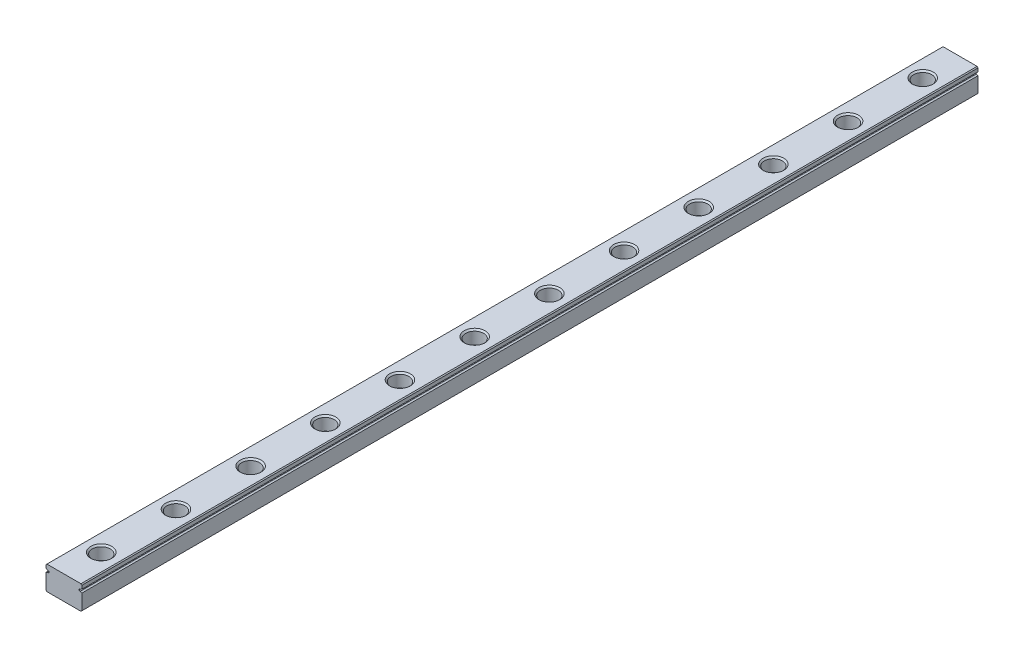
SolidWorks part; units mm, degrees
material "AISI 1045 鋼，冷拉"
ref_plane "Front Plane" through (0, 0, 0) normal (0, 0, 1) x (1, 0, 0)
ref_plane "Top Plane" through (0, 0, 0) normal (0, 1, 0) x (1, 0, 0)
ref_plane "Right Plane" through (0, 0, 0) normal (1, 0, 0) x (0, 0, -1)
sketch "Sketch1" plane through (0, 0, 0) normal (0, 0, 1) x (1, 0, 0)
  line L0 (-6, -4) -> (-6, 4) construction
  line L1 (-6, 4) -> (6, 4)
  line L2 (-6, -4) -> (6, -4)
  line L3 (-6, 4) -> (-6, 2.75)
  line L4 (-6, 2.75) -> (-5.5, 2.25) construction
  line L5 (-5.5, 2.25) -> (-5, 2.25)
  line L6 (-5.5, 1.75) -> (-6, 1.25) construction
  line L7 (-6, 1.25) -> (-6, -4)
  line L8 (-5, 2.25) -> (-5, 1.75)
  line L9 (-5, 1.75) -> (-5.5, 1.75)
  line L10 (-5.5, 1.75) -> (-5.25, 2) construction
  line L11 (-5.25, 2) -> (-5.5, 2.25) construction
  line L12 (-6, 2.75) -> (-6, 2.559)
  line L13 (-6, 1.25) -> (-6, 1.441)
  line L14 (0, 4) -> (0, -4) construction
  line L15 (5.25, 2) -> (5.5, 2.25) construction
  line L16 (5.5, 1.75) -> (5.25, 2) construction
  line L17 (5.5, 1.75) -> (6, 1.25) construction
  line L18 (6, 2.75) -> (5.5, 2.25) construction
  line L19 (6, -4) -> (6, 4) construction
  line L20 (6, 1.25) -> (6, 1.441)
  line L21 (6, 2.75) -> (6, 2.559)
  line L22 (5, 1.75) -> (5.5, 1.75)
  line L23 (5, 2.25) -> (5, 1.75)
  line L24 (6, 1.25) -> (6, -4)
  line L25 (5.5, 2.25) -> (5, 2.25)
  line L26 (6, 4) -> (6, 2.75)
  arc A0 (-6, 1.441) -> (-5.5, 1.75) centre (-6, 2) ccw
  arc A1 (-5.5, 2.25) -> (-6, 2.559) centre (-6, 2) ccw
  arc A2 (5.5, 2.25) -> (6, 2.559) centre (6, 2) cw
  arc A3 (6, 1.441) -> (5.5, 1.75) centre (6, 2) cw
  point P4 (-5, 2)
  point P28 (5, 2)
  dimension "D1" = 8
  dimension "D2" = 6
  dimension "D3" = 0.5
  dimension "D4" = 45
  dimension "D5" = 2
  dimension "D6" = 1
extrude "Boss-Extrude1" add sketch "Sketch1" along normal blind 300
chamfer "Chamfer1" distance 0.3 angle 45 4 edges at (-6, -4, 150) (6, -4, 150) (-6, 4, 150) (6, 4, 150)
hole_wizard "M3 六角承窩頭蓋螺釘的柱孔1" positions "3DSketch1" profile "Sketch3" counterbore size "M3" standard "ISO" end condition through all
sketch3d "3DSketch1"
  line L0 (0, 4, 0) -> (0, 4, 12.5) construction
  line L1 (5.7, 4, 0) -> (-5.7, 4, 0) construction
  point P0 (0, 4, 12.5)
  dimension "D1" = 12.5
sketch "Sketch3" plane through (0, 4, 12.5) normal (1, 0, 0) x (0, 0, 1)
  line L0 (0, 0) -> (0, 8)
  line L1 (1.75, 7.75) -> (2, 8)
  line L2 (3, 4.5) -> (1.75, 4.5)
  line L3 (1.75, 4.5) -> (1.75, 7.75)
  line L5 (3, 4.5) -> (3, 0.5)
  line L6 (3, 0.5) -> (3.5, 0)
  line L7 (3.5, 0) -> (0, 0)
  line L8 (-3, 0.5) -> (-3.5, 0) construction
  line L11 (0, -6.35) -> (0, 107.95) construction
  line L12 (2, 8) -> (0, 8)
  line L13 (-1.75, 7.75) -> (-2, 8) construction
  dimension "Thru Hole Dia." = 3.5
  dimension "Thru Hole Depth" = 8
  dimension "C'Bore Dia." = 6
  dimension "C'Bore Depth" = 4.5
  dimension "Near C'Sink Dia." = 7
  dimension "Near C'Sink Angle" = 90
  dimension "Far C'Sink Dia." = 4
  dimension "Far C'Sink Angle" = 90
pattern_linear "LPattern1" count 12 spacing 25 along (0, 0, 1) of "M3 六角承窩頭蓋螺釘的柱孔1"
